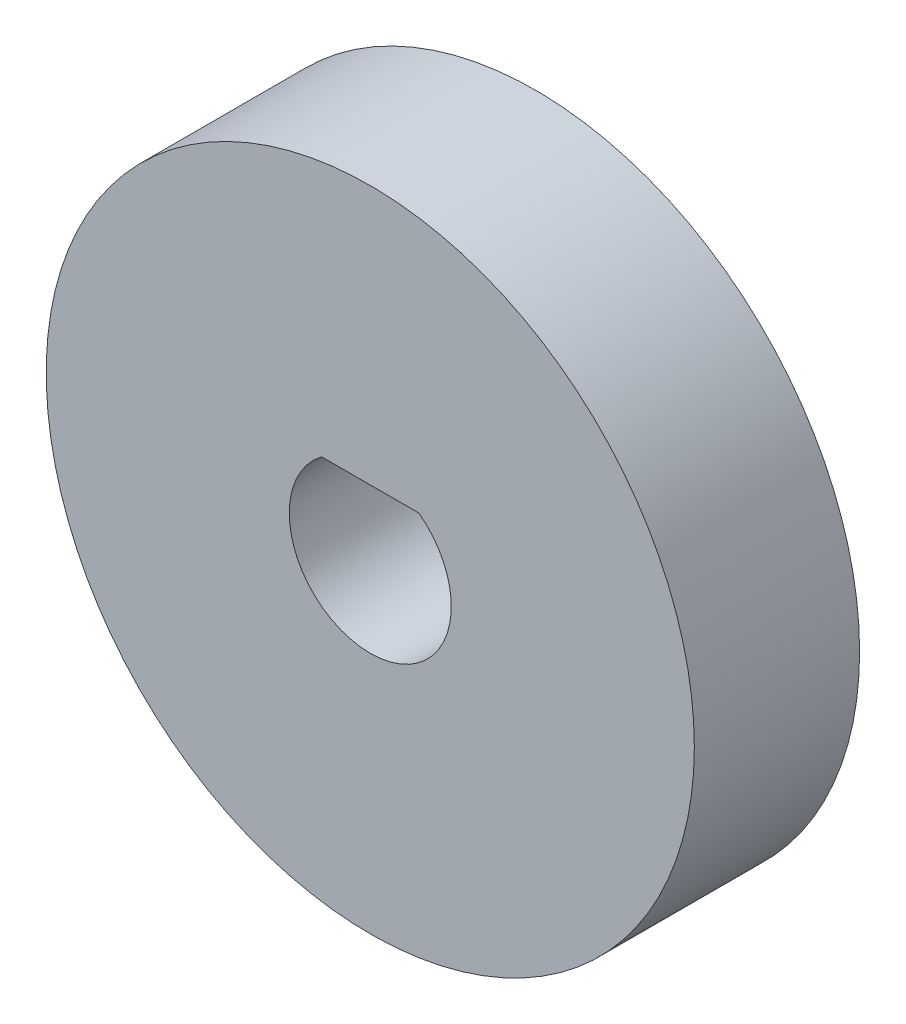
SolidWorks part; units mm, degrees
ref_plane "Front Plane" through (0, 0, 0) normal (0, 0, 1) x (1, 0, 0)
ref_plane "Top Plane" through (0, 0, 0) normal (0, 1, 0) x (1, 0, 0)
ref_plane "Right Plane" through (0, 0, 0) normal (1, 0, 0) x (0, 0, -1)
sketch "Sketch1" plane through (0, 0, 0) normal (0, 0, 1) x (1, 0, 0)
  line L0 (-1.5, 2) -> (1.5, 2)
  circle A0 centre (0, 0) radius 10
  arc A1 (-1.5, 2) -> (1.5, 2) centre (0, 0) ccw
  dimension "D1" = 20
  dimension "D2" = 5
  dimension "D3" = 2
extrude "Boss-Extrude1" add sketch "Sketch1" along normal blind 5.1
